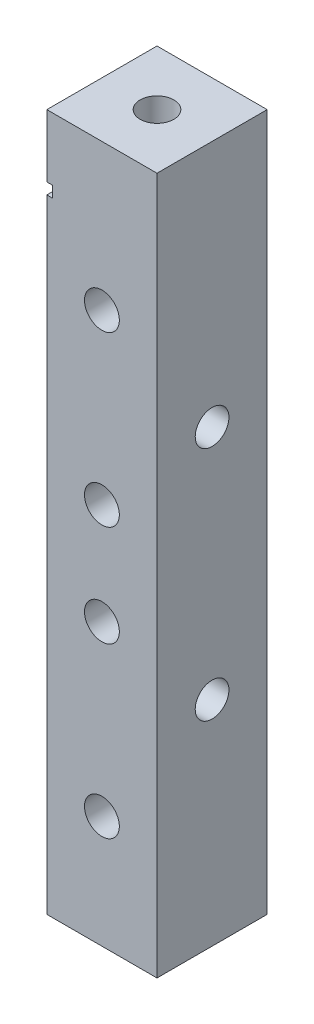
SolidWorks part; units mm, degrees
ref_plane "Ebene vorne" through (0, 0, 0) normal (0, 0, 1) x (1, 0, 0)
ref_plane "Ebene oben" through (0, 0, 0) normal (0, 1, 0) x (1, 0, 0)
ref_plane "Ebene rechts" through (0, 0, 0) normal (1, 0, 0) x (0, 0, -1)
sketch "Sketch1" plane through (0, 0, 0) normal (0, 1, 0) x (1, 0, 0)
  line L1 (-4.9, -4.9) -> (4.9, -4.9)
  line L2 (-4.9, -4.9) -> (-4.9, 4.9)
  line L3 (-4.9, 4.9) -> (4.9, 4.9)
  line L4 (4.9, -4.9) -> (4.9, 4.9)
  line L5 (-4.9, -4.9) -> (4.9, 4.9) construction
  line L6 (-4.9, 4.9) -> (4.9, -4.9) construction
  point P0 (0, 0)
  dimension "D1" = 9.8
  dimension "D2" = 9.8
extrude "Extrude1" add sketch "Sketch1" along normal blind 62
sketch "Sketch2" plane through (0, 0, 0) normal (0, -1, 0) x (1, 0, 0)
  circle A0 centre (0, 0) radius 1.5
  dimension "D1" = 3
extrude "Extrude2" cut sketch "Sketch2" against normal blind 10
sketch "Sketch3" plane through (0, 62, 0) normal (0, 1, 0) x (1, 0, 0)
  circle A0 centre (0, 0) radius 1.5
  dimension "D1" = 3
extrude "Extrude3" cut sketch "Sketch3" against normal blind 10
sketch "Sketch4" plane through (0, 0, -4.9) normal (0, 0, -1) x (-1, 0, 0)
  line L0 (-4.9, 62) -> (4.9, 62) construction
  line L1 (-4.9, 0) -> (4.9, 0) construction
  circle A0 centre (0, 10) radius 1.55
  circle A1 centre (0, 49) radius 1.55
  circle A2 centre (0, 34) radius 1.55
  circle A3 centre (0, 25) radius 1.55
  dimension "D1" = 3.1
  dimension "D2" = 3.1
  dimension "D5" = 3.1
  dimension "D6" = 3.1
  dimension "D3" = 13
  dimension "D4" = 10
  dimension "D7" = 15
  dimension "D8" = 15
extrude "Extrude4" cut sketch "Sketch4" against normal blind 10
sketch "Sketch5" plane through (-4.9, 0, 0) normal (-1, 0, 0) x (0, 0, 1)
  line L0 (-4.9, 62) -> (4.9, 62) construction
  line L1 (-4.9, 0) -> (4.9, 0) construction
  circle A0 centre (0, 40) radius 1.5
  circle A1 centre (0, 19) radius 1.5
  dimension "D1" = 3
  dimension "D2" = 3
  dimension "D3" = 22
  dimension "D4" = 19
extrude "Extrude5" cut sketch "Sketch5" against normal blind 10
sketch "Sketch6" plane through (-4.9, 0, 0) normal (-1, 0, 0) x (0, 0, 1)
  line L1 (-4.9, 55.4276) -> (4.9, 55.4276)
  line L2 (-4.9, 55.4276) -> (-4.9, 56.4276)
  line L3 (-4.9, 56.4276) -> (4.9, 56.4276)
  line L4 (4.9, 55.4276) -> (4.9, 56.4276)
  line L6 (-4.9, 62) -> (-4.9, 0) construction
  line L7 (4.9, 62) -> (4.9, 0) construction
  dimension "D1" = 1
  dimension "D2" = 9.8
extrude "Extrude6" cut sketch "Sketch6" against normal blind 0.5
